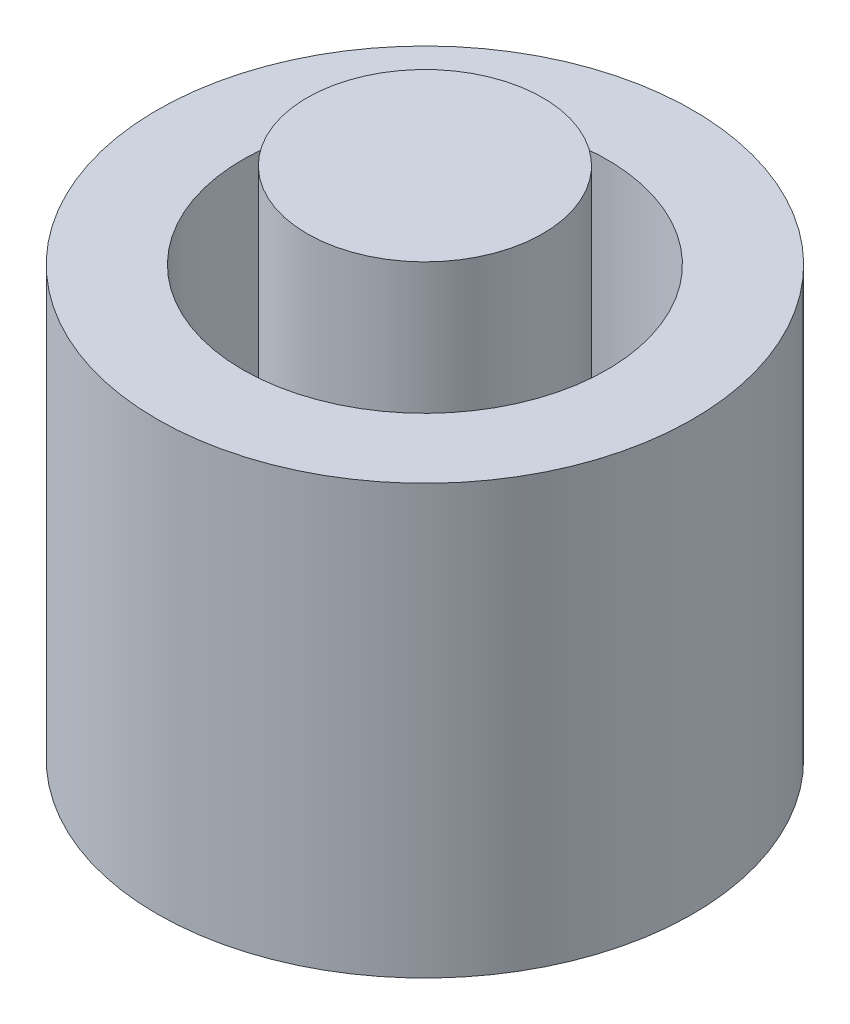
SolidWorks part; units mm, degrees
ref_plane "前视基准面" through (0, 0, 0) normal (0, 0, 1) x (1, 0, 0)
ref_plane "上视基准面" through (0, 0, 0) normal (0, 1, 0) x (1, 0, 0)
ref_plane "右视基准面" through (0, 0, 0) normal (1, 0, 0) x (0, 0, -1)
sketch "草图1" plane through (0, 0, 0) normal (0, 1, 0) x (1, 0, 0)
  circle A1 centre (0, 0) radius 6.25
extrude "凸台-拉伸2" add sketch "草图1" along normal blind 10
shell "抽壳1" thickness 2
sketch "草图2" plane through (0, 2, 0) normal (0, 1, 0) x (1, 0, 0)
  circle A0 centre (0, 0) radius 2.75
extrude "凸台-拉伸3" add sketch "草图2" along normal blind 10
